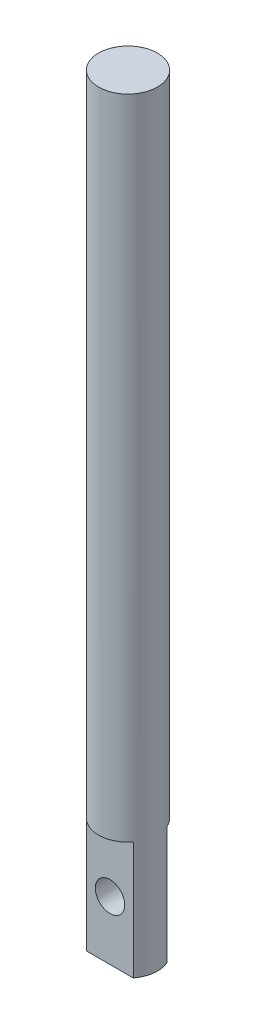
SolidWorks part; units mm, degrees
ref_plane "Plan de face" through (0, 0, 0) normal (0, 0, 1) x (1, 0, 0)
ref_plane "Plan de dessus" through (0, 0, 0) normal (0, 1, 0) x (1, 0, 0)
ref_plane "Plan de droite" through (0, 0, 0) normal (1, 0, 0) x (0, 0, -1)
sketch "Esquisse1" plane through (0, 0, 0) normal (0, 1, 0) x (1, 0, 0)
  circle A0 centre (0, 0) radius 5
extrude "Boss.-Extru.1" add sketch "Esquisse1" along normal blind 130
sketch "Esquisse2" plane through (0, 0, 0) normal (0, -1, 0) x (-1, 0, 0)
  line L0 (4.5826, 2) -> (-4.5826, 2)
  line L1 (4.5826, -2) -> (-4.5826, -2)
  line L2 (4.5826, -2) -> (4.5826, 2)
  line L3 (4.5826, 2) -> (-4.5826, 2)
  line L4 (-4.5826, -2) -> (-4.5826, 2)
  circle A0 centre (0, 0) radius 5 construction
  arc A1 (-4.5826, 2) -> (4.5824, 2.0005) centre (0, 0) cw
  arc A2 (-4.5826, 2) -> (4.5826, 2) centre (0, 0) cw
  circle M3 centre (0, 0) radius 5
  dimension "D1" = 4
  dimension "D2" = 5
extrude "Enlèv. mat.-Extru.2" cut sketch "Esquisse2" against normal blind 20 contours L0 M3
sketch "Esquisse3" plane through (0, 0, 0) normal (0, -1, 0) x (1, 0, 0)
  line L1 (-3.9551, -0.9411) -> (3.9551, -0.9411)
  line L2 (-3.9551, -0.9411) -> (-3.9551, 3.0589)
  line L3 (-3.9551, 3.0589) -> (3.9551, 3.0589)
  line L4 (3.9551, -0.9411) -> (3.9551, 3.0589)
  arc A0 (3.9551, 3.0589) -> (-3.9551, 3.0589) centre (0, 0) ccw
  arc M3 (4.5826, -2) -> (-4.5826, -2) centre (0, 0) ccw
  dimension "D1" = 4
  dimension "D2" = 5
  dimension "D3" = 5
extrude "Enlèv. mat.-Extru.3" cut sketch "Esquisse3" against normal blind 20 contours L3 M3
sketch "Esquisse4" plane through (0, 0, 3.0589) normal (0, 0, 1) x (1, 0, 0)
  line L0 (-3.9551, 0) -> (3.9551, 0) construction
  line L1 (3.9551, 20) -> (3.9551, 0) construction
  circle A0 centre (0.0051, 10) radius 2.5
  dimension "D1" = 5
  dimension "D2" = 10
  dimension "D3" = 3.95
extrude "Enlèv. mat.-Extru.4" cut sketch "Esquisse4" against normal blind 60
